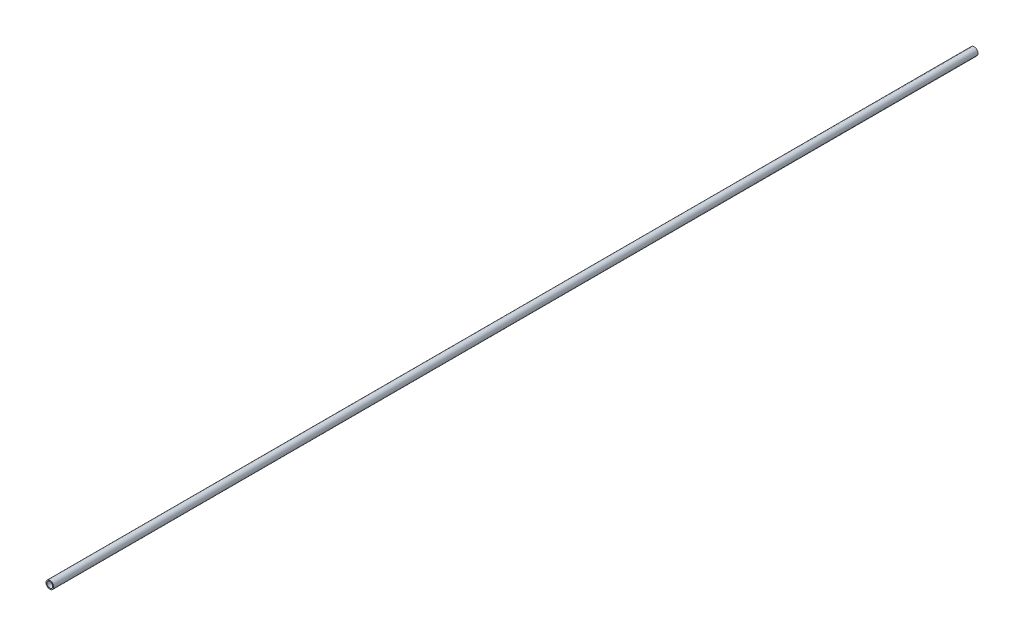
SolidWorks part; units mm, degrees
ref_plane "Front Plane" through (0, 0, 0) normal (0, 0, 1) x (1, 0, 0)
ref_plane "Top Plane" through (0, 0, 0) normal (0, 1, 0) x (1, 0, 0)
ref_plane "Right Plane" through (0, 0, 0) normal (1, 0, 0) x (0, 0, -1)
sketch "Sketch1" plane through (0, 0, 0) normal (0, 0, 1) x (1, 0, 0)
  circle A0 centre (0, 0) radius 6.35 construction
  circle A1 centre (0, 0) radius 4.7625 construction
  point P3 (-6.35, 0)
  point P4 (6.35, 0)
  point P6 (-4.7625, 0)
  point P7 (4.7625, 0)
  dimension "OD" = 12.7
  dimension "ID" = 9.525
  dimension "Wall Thickness" = 1.5875
sketch "Sketch2" plane through (0, 0, 0) normal (1, 0, 0) x (0, 0, -1)
  line L0 (762, 0) -> (-762, 0) construction
  line L2 (0, 6.35) -> (0, -6.35) construction
  line L3 (0, 6.35) -> (0, -6.35) construction
  line L4 (762, 6.35) -> (-762, 6.35) construction
  line L5 (762, -6.35) -> (-762, -6.35) construction
  line L6 (-762, -6.35) -> (-762, 6.35) construction
  line L7 (762, -6.35) -> (762, 6.35) construction
  line L8 (-749.3, -6.35) -> (-749.3, 6.35) construction
  line L9 (749.3, -6.35) -> (749.3, 6.35) construction
  point P3 (0, 0)
  point P9 (0, 6.35)
  point P11 (0, -6.35)
  point P13 (-762, 0)
  point P14 (762, 6.35)
  point P15 (-762, -6.35)
  point P16 (-762, 6.35)
  point P17 (-762, 0)
  point P18 (762, -6.35)
  point P19 (762, 0)
  point P22 (-749.3, 0)
  point P25 (749.3, 0)
  point P26 (-749.3, -6.35)
  point P27 (-749.3, 6.35)
  point P28 (749.3, 6.35)
  point P29 (749.3, -6.35)
  dimension "Length" = 1524
  dimension "D1" = 12.7
sketch "Sketch3" plane through (0, 0, 0) normal (0, 0, 1) x (1, 0, 0)
  circle A0 centre (0, 0) radius 6.35 construction
  circle A1 centre (0, 0) radius 4.7625 construction
  circle A2 centre (0, 0) radius 6.35
  circle A3 centre (0, 0) radius 4.7625
extrude "Boss-Extrude1" add sketch "Sketch3" along normal mid plane 1524
equation "\"D1@Sketch2\"=\"OD@Sketch1\""
equation "\"D1@Boss-Extrude1\"=\"Length@Sketch2\""
